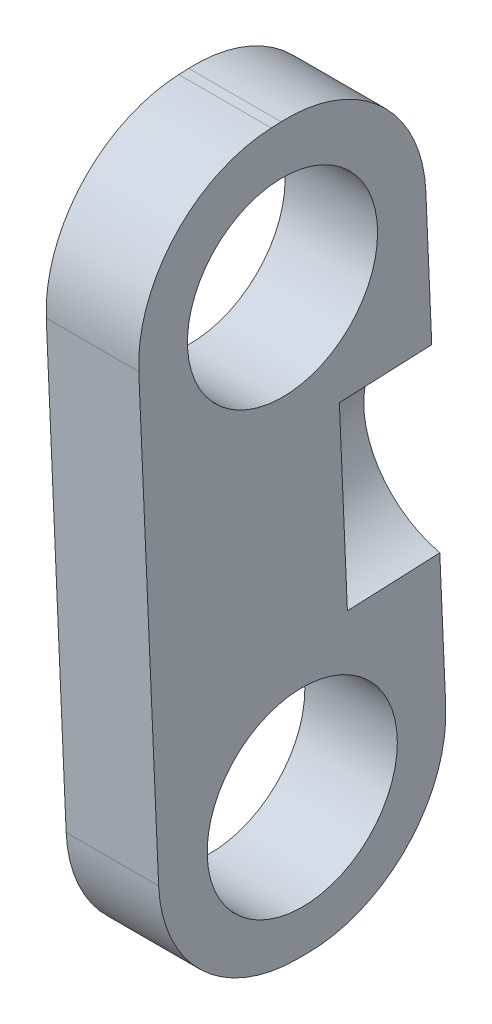
SolidWorks part; units mm, degrees
material "ABS"
ref_plane "Front Plane" through (0, 0, 0) normal (0, 0, 1) x (1, 0, 0)
ref_plane "Top Plane" through (0, 0, 0) normal (0, 1, 0) x (1, 0, 0)
ref_plane "Right Plane" through (0, 0, 0) normal (1, 0, 0) x (0, 0, -1)
sketch "Sketch1" plane through (0, 0, 0) normal (1, 0, 0) x (0, 0, -1)
  line L0 (0, 0) -> (177.8, 0) construction
  line L1 (0, 0) -> (177.1234, 15.4963) construction
  line L2 (183.1817, 7.9979) -> (182.8874, 14.7383) construction
  line L3 (182.8874, 14.7383) -> (190.8174, 15.0846) construction
  line L4 (0, 0) -> (187.1467, 8.171) construction
  line L5 (190.8174, 15.0846) -> (191.406, 1.6037) construction
  line L6 (191.406, 1.6037) -> (183.476, 1.2574) construction
  line L7 (183.476, 1.2574) -> (183.1817, 7.9979) construction
  line L8 (182.8874, 14.7383) -> (191.406, 1.6037) construction
  line L9 (191.406, 1.6037) -> (190.8174, 15.0846) construction
  line L10 (190.8174, 15.0846) -> (183.476, 1.2574) construction
  line L11 (183.1817, 7.9979) -> (180.0098, 7.8594) construction
  line L12 (180.0098, 7.8594) -> (179.8674, 11.1202) construction
  line L13 (179.8674, 11.1202) -> (183.0394, 11.2587) construction
  line L14 (180.0098, 7.8594) -> (180.1521, 4.5986) construction
  line L15 (180.1521, 4.5986) -> (183.3241, 4.7371) construction
  line L16 (177.1234, 15.4963) -> (177.8, 0) construction
  line L17 (182.3887, 7.9633) -> (181.8348, 20.6512)
  line L18 (181.8348, 20.6512) -> (171.9807, 20.2209)
  line L19 (182.3887, 7.9633) -> (182.9427, -4.7246)
  line L20 (182.9427, -4.7246) -> (173.0699, -4.7246)
  line L21 (173.0699, -4.7246) -> (171.9807, 20.2209)
  line L22 (177.1234, 15.4963) -> (176.9077, 20.4361) construction
  line L23 (177.8, 0) -> (178.0063, -4.7246) construction
  circle A0 centre (177.1234, 15.4963) radius 3.2639
  circle A1 centre (177.8, 0) radius 3.2639
  point P23 (181.4534, 11.1894)
  point P24 (176.9077, 20.4361)
  dimension "D4" = 6.5278
  dimension "D5" = 6.5278
  dimension "D1" = 177.8
  dimension "D2" = 5
  dimension "D3" = 177.8
  dimension "D6" = 187.325
  dimension "D7" = 7.9375
  dimension "D8" = 13.4937
  dimension "D9" = 3.175
  dimension "D10" = 6.5278
  dimension "D11" = 2.5
  dimension "D12" = 12.7
  dimension "D14" = 12.7
  dimension "D16" = 0.7937
extrude "Boss-Extrude1" add sketch "Sketch1" along normal blind 3.175
fillet "Fillet2" radius 4.7625 4 edges at (1.5875, 20.6512, -181.8348) (1.5875, -4.7246, -182.9427) (1.5875, -4.7246, -173.0699) (1.5875, 20.2209, -171.9807)
sketch "Sketch3" plane through (0, 7.9633, -182.3887) normal (0, 0.0436, -0.999) x (-1, 0, 0)
  line L0 (0, 0.1062) -> (-3.9688, 0.1062) construction
  line L1 (0, -7.725) -> (0, 7.9375) construction
  circle A0 centre (-3.9688, 0.1062) radius 3.2639
  point P5 (-8.9548, 0)
  dimension "D2" = 6.5278
  dimension "D1" = 3.9688
extrude "Cut-Extrude1" cut sketch "Sketch3" against normal blind 3.175
